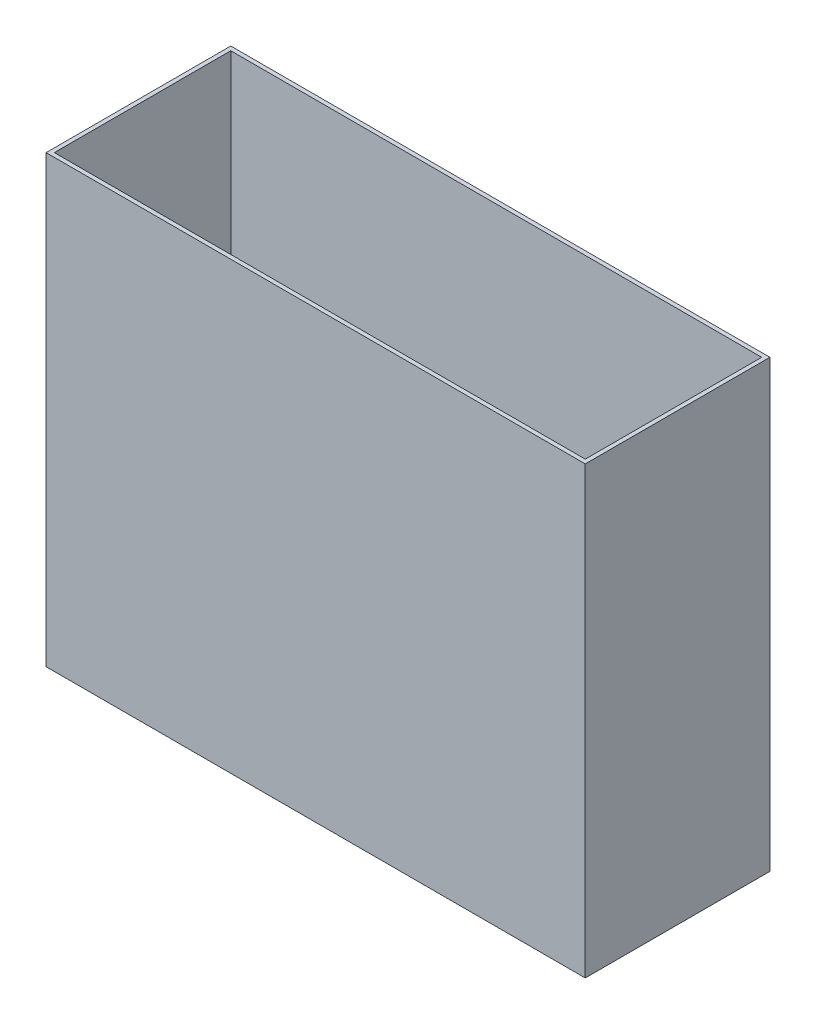
SolidWorks part; units mm, degrees
ref_plane "Plano frontal" through (0, 0, 0) normal (0, 0, 1) x (1, 0, 0)
ref_plane "Plano superior" through (0, 0, 0) normal (0, 1, 0) x (1, 0, 0)
ref_plane "Plano direito" through (0, 0, 0) normal (1, 0, 0) x (0, 0, -1)
sketch "Esboço1" plane through (0, 0, 0) normal (0, 1, 0) x (1, 0, 0)
  line L0 (0, 0) -> (337, 0)
  line L1 (337, 0) -> (337, 112)
  line L2 (337, 112) -> (0, 112)
  line L3 (0, 112) -> (0, 0)
extrude "Ressalto-extrusão1" add sketch "Esboço1" along normal blind 280
shell "Casca1" thickness 2.6
